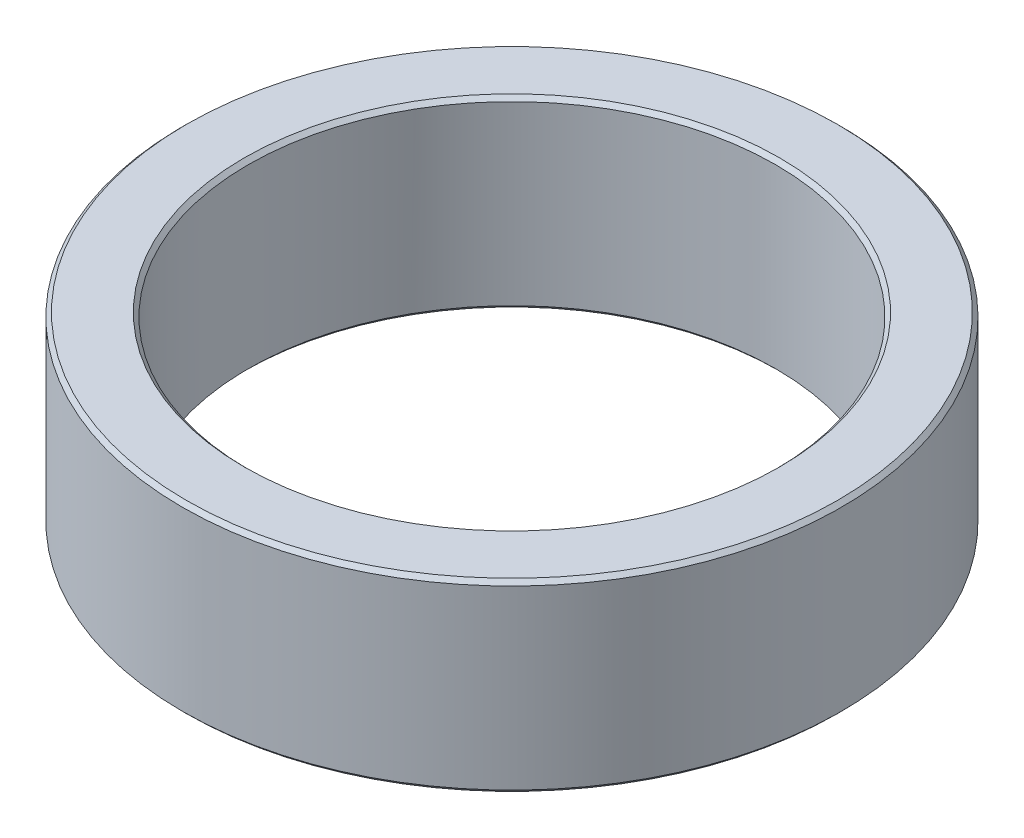
SolidWorks part; units mm, degrees
ref_plane "Front Plane" through (0, 0, 0) normal (0, 0, 1) x (1, 0, 0)
ref_plane "Top Plane" through (0, 0, 0) normal (0, 1, 0) x (1, 0, 0)
ref_plane "Right Plane" through (0, 0, 0) normal (1, 0, 0) x (0, 0, -1)
sketch "Sketch1" plane through (0, 0, 0) normal (0, 1, 0) x (1, 0, 0)
  circle A0 centre (0, 0) radius 12.495
  circle A1 centre (0, 0) radius 10
  dimension "D1" = 24.99
  dimension "D2" = 20
extrude "Boss-Extrude1" add sketch "Sketch1" along normal blind 7
chamfer "Chamfer1" distance 0.15 angle 45 4 edges at (0, 0, 10) (0, 0, 12.495) (0, 7, 10) (0, 7, 12.495)
